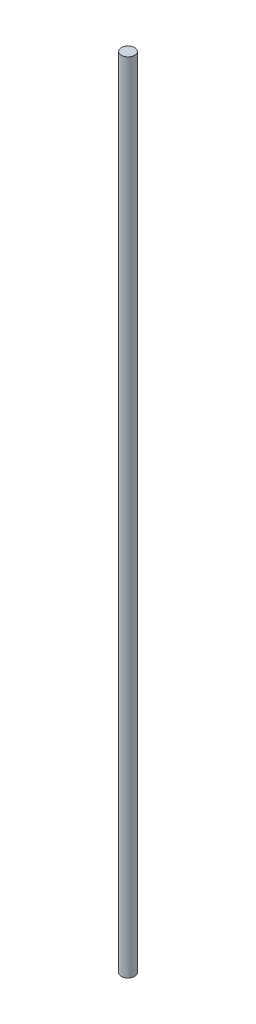
SolidWorks part; units mm, degrees
ref_plane "Спереди" through (0, 0, 0) normal (0, 0, 1) x (1, 0, 0)
ref_plane "Сверху" through (0, 0, 0) normal (0, 1, 0) x (1, 0, 0)
ref_plane "Справа" through (0, 0, 0) normal (1, 0, 0) x (0, 0, -1)
sketch "Эскиз1" plane through (0, 0, 0) normal (0, 1, 0) x (1, 0, 0)
  circle A0 centre (0, 0) radius 0.1
  dimension "D1" = 0.2
extrude "Бобышка-Вытянуть1" add sketch "Эскиз1" along normal blind 12
